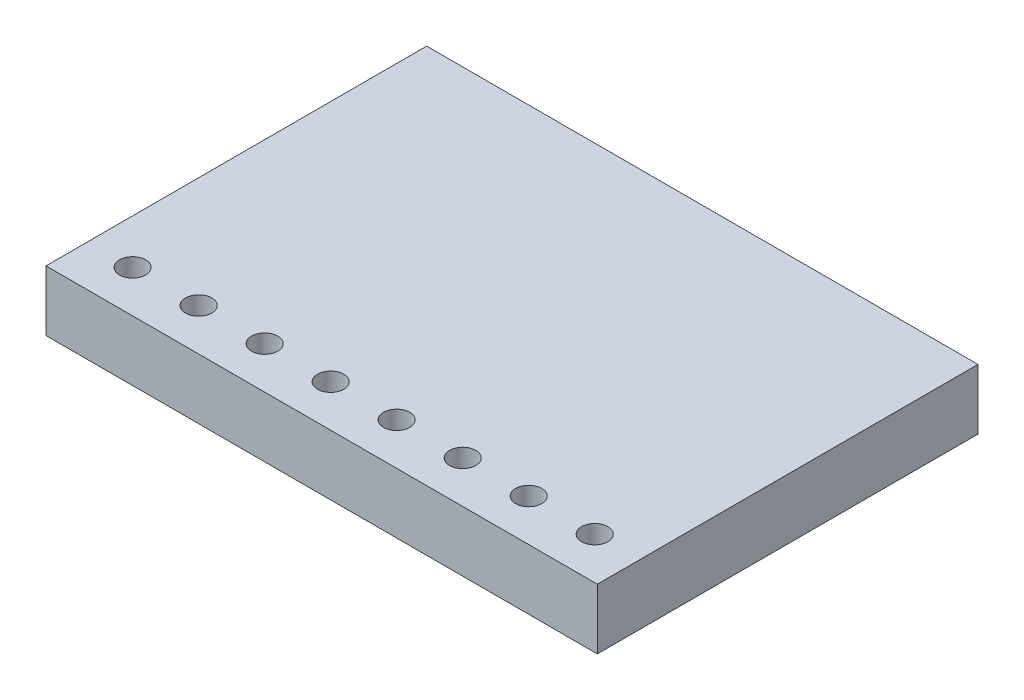
SolidWorks part; units mm, degrees
ref_plane "Спереди" through (0, 0, 0) normal (0, 0, 1) x (1, 0, 0)
ref_plane "Сверху" through (0, 0, 0) normal (0, 1, 0) x (1, 0, 0)
ref_plane "Справа" through (0, 0, 0) normal (1, 0, 0) x (0, 0, -1)
other "Configuration Table"
sketch "Эскиз1" plane through (0, 0, 0) normal (0, 1, 0) x (1, 0, 0)
  line L1 (-10.5, -7.25) -> (10.5, -7.25)
  line L2 (-10.5, -7.25) -> (-10.5, 7.25)
  line L3 (-10.5, 7.25) -> (10.5, 7.25)
  line L4 (10.5, -7.25) -> (10.5, 7.25)
  line L5 (-10.5, -7.25) -> (10.5, 7.25) construction
  line L6 (-10.5, 7.25) -> (10.5, -7.25) construction
  point P0 (0, 0)
  dimension "D1" = 21
  dimension "D2" = 14.5
extrude "Бобышка-Вытянуть1" add sketch "Эскиз1" along normal blind 2.3
sketch "Эскиз2" plane through (0, 2.3, 0) normal (0, 1, 0) x (1, 0, 0)
  line L0 (-10.5, -7.25) -> (10.5, -7.25) construction
  line L1 (-10.5, 7.25) -> (-10.5, -7.25) construction
  line L2 (10.5, -7.25) -> (10.5, 7.25) construction
  circle A0 centre (-8.8, -5.65) radius 0.5
  circle A1 centre (-6.2857, -5.65) radius 0.5
  circle A2 centre (-3.7714, -5.65) radius 0.5
  circle A3 centre (-1.2571, -5.65) radius 0.5
  circle A4 centre (1.2571, -5.65) radius 0.5
  circle A5 centre (3.7714, -5.65) radius 0.5
  circle A6 centre (6.2857, -5.65) radius 0.5
  circle A7 centre (8.8, -5.65) radius 0.5
  dimension "D1" = 1
  dimension "D2" = 1.6
  dimension "D3" = 1.7
  dimension "D5" = 17.6
  dimension "D6" = 1.7
  dimension "D4" = 8
extrude "Вырез-Вытянуть1" cut sketch "Эскиз2" against normal through all
